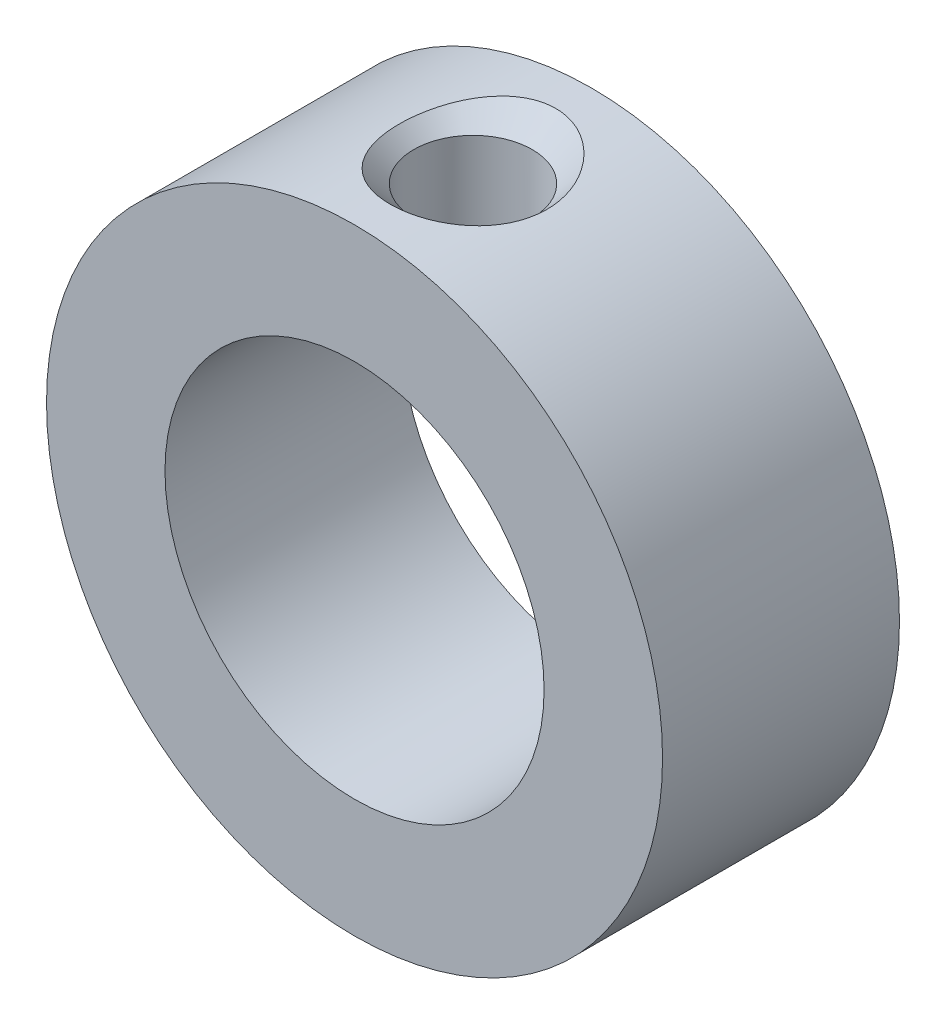
SolidWorks part; units mm, degrees
material "Plain Carbon Steel"
ref_plane "Front Plane" through (0, 0, 0) normal (0, 0, 1) x (1, 0, 0)
ref_plane "Top Plane" through (0, 0, 0) normal (0, 1, 0) x (1, 0, 0)
ref_plane "Right Plane" through (0, 0, 0) normal (1, 0, 0) x (0, 0, -1)
sketch "Sketch1" plane through (0, 0, 0) normal (0, 0, 1) x (1, 0, 0)
  circle A0 centre (0, 0) radius 20.6375
  circle A1 centre (0, 0) radius 12.7
  dimension "D1" = 25.4
  dimension "D2" = 41.275
extrude "Boss-Extrude1" add sketch "Sketch1" along normal mid plane 15.875
sketch "Sketch3" plane through (0, 0, 0) normal (0, 0, 1) x (1, 0, 0)
  line L0 (0, 0) -> (0, 24.8791)
  line L1 (0, 24.8791) -> (-9.7978, 24.8791)
  line L2 (-9.7978, 24.8791) -> (-3.9688, 19.05)
  line L3 (-3.9688, 19.05) -> (-3.9687, 0)
  line L4 (-3.9687, 0) -> (0, 0)
  dimension "D1" = 3.9688
  dimension "D2" = 45
  dimension "D3" = 19.05
revolve "Cut-Revolve1" cut sketch "Sketch3" angle 360 about L0
